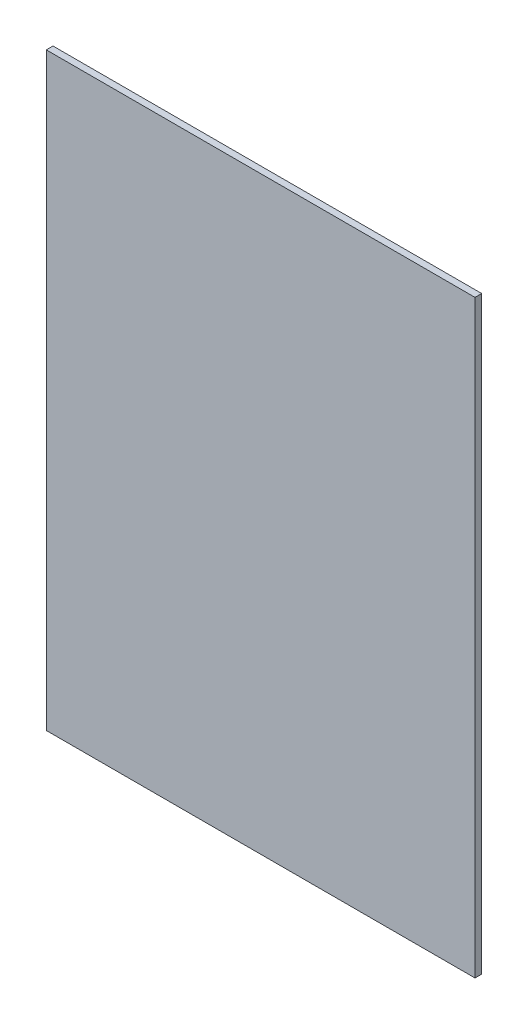
SolidWorks part; units mm, degrees
ref_plane "Front Plane" through (0, 0, 0) normal (0, 0, 1) x (1, 0, 0)
ref_plane "Top Plane" through (0, 0, 0) normal (0, 1, 0) x (1, 0, 0)
ref_plane "Right Plane" through (0, 0, 0) normal (1, 0, 0) x (0, 0, -1)
sketch "Sketch1" plane through (0, 0, 0) normal (0, 0, 1) x (1, 0, 0)
  line L1 (0, 0) -> (203.2, 0)
  line L2 (0, 0) -> (0, 279.4)
  line L3 (0, 279.4) -> (203.2, 279.4)
  line L4 (203.2, 0) -> (203.2, 279.4)
  dimension "D1" = 279.4
  dimension "D2" = 203.2
extrude "Boss-Extrude4" add sketch "Sketch1" along normal blind 3.175 contours L2 L1 L4 L3
sketch "Sketch2" plane through (0, 0, 0) normal (0, 0, -1) x (-1, 0, 0)
  line L1 (-31.3936, 249.2049) -> (-2.1836, 249.2049)
  line L2 (-31.3936, 249.2049) -> (-31.3936, 255.5549)
  line L3 (-31.3936, 255.5549) -> (-2.1836, 255.5549)
  line L4 (-2.1836, 249.2049) -> (-2.1836, 255.5549)
  line L26 (-121.6341, 269.3831) -> (-96.2341, 269.3831)
  line L27 (-121.6341, 269.3831) -> (-121.6341, 275.6569)
  line L28 (-121.6341, 275.6569) -> (-96.2341, 275.6569)
  line L29 (-96.2341, 269.3831) -> (-96.2341, 275.6569)
  line L31 (-95.0721, 245.7573) -> (-84.9121, 245.7573)
  line L32 (-95.0721, 245.7573) -> (-95.0721, 261.7593)
  line L33 (-95.0721, 261.7593) -> (-84.9121, 261.7593)
  line L34 (-84.9121, 245.7573) -> (-84.9121, 261.7593)
  line L35 (-89.1031, 253.8853) -> (-86.1821, 253.8853)
  line L36 (-89.1031, 253.8853) -> (-89.1031, 247.5353)
  line L37 (-89.1031, 247.5353) -> (-86.1821, 247.5353)
  line L38 (-86.1821, 253.8853) -> (-86.1821, 247.5353)
  line L40 (-112.6436, 266.3285) -> (-107.5636, 266.3285)
  line L41 (-112.6436, 266.3285) -> (-112.6436, 234.5785)
  line L42 (-112.6436, 234.5785) -> (-107.5636, 234.5785)
  line L43 (-107.5636, 266.3285) -> (-107.5636, 234.5785)
  line L44 (-138.0871, 270.3021) -> (-161.5231, 278.0823)
  line L45 (-161.5231, 278.0823) -> (-170.4131, 270.4623)
  line L46 (-170.4131, 270.4623) -> (-170.4131, 262.3343)
  line L47 (-170.4131, 262.3343) -> (-166.5711, 262.3343)
  line L48 (-166.5711, 262.3343) -> (-166.5711, 265.9961)
  line L49 (-166.5711, 265.9961) -> (-161.7499, 270.1286)
  line L50 (-161.7499, 270.1286) -> (-140.4879, 263.0702)
  line L51 (-140.4879, 263.0702) -> (-138.0871, 270.3021)
  line L61 (-186.5536, 277.0345) -> (-178.4256, 277.0345)
  line L62 (-186.5536, 277.0345) -> (-186.5536, 246.5545)
  line L63 (-186.5536, 246.5545) -> (-178.4256, 246.5545)
  line L64 (-178.4256, 277.0345) -> (-178.4256, 246.5545)
  line L80 (-49.3409, 261.2356) -> (-49.3409, 277.1106)
  line L81 (-49.3409, 261.2356) -> (-78.5509, 261.2356)
  line L82 (-78.5509, 261.2356) -> (-78.5509, 269.4899)
  line L83 (-78.5509, 269.4899) -> (-56.9609, 269.4899)
  line L84 (-56.9609, 269.4899) -> (-56.9609, 277.1106)
  line L85 (-56.9609, 277.1106) -> (-49.3409, 277.1106)
  line L86 (-54.8019, 269.3636) -> (-51.8809, 269.3636)
  line L87 (-54.8019, 269.3636) -> (-54.8019, 263.0136)
  line L88 (-54.8019, 263.0136) -> (-51.8809, 263.0136)
  line L89 (-51.8809, 269.3636) -> (-51.8809, 263.0136)
  line L91 (-57.5959, 262.7596) -> (-75.3759, 262.7596)
  line L92 (-57.5959, 262.7596) -> (-57.5959, 265.6806)
  line L93 (-57.5959, 265.6806) -> (-75.3759, 265.6806)
  line L94 (-75.3759, 262.7596) -> (-75.3759, 265.6806)
  line L98 (-31.4092, 264.742) -> (-2.1283, 264.742)
  line L99 (-31.4092, 264.742) -> (-31.4092, 271.1591)
  line L100 (-31.4092, 271.1591) -> (-2.1283, 271.1591)
  line L101 (-2.1283, 264.742) -> (-2.1283, 271.1591)
  line L102 (-31.3383, 256.868) -> (-2.1283, 256.868)
  line L103 (-31.3383, 256.868) -> (-31.3383, 263.218)
  line L104 (-31.3383, 263.218) -> (-2.1283, 263.218)
  line L105 (-2.1283, 256.868) -> (-2.1283, 263.218)
  line L106 (-198.4619, 276.9896) -> (-190.3339, 276.9896)
  line L107 (-198.4619, 276.9896) -> (-198.4619, 246.5096)
  line L108 (-198.4619, 246.5096) -> (-190.3339, 246.5096)
  line L109 (-190.3339, 276.9896) -> (-190.3339, 246.5096)
  line L114 (-147.2846, 270.8129) -> (-154.9986, 273.3738)
  line L115 (-154.9986, 273.3738) -> (-155.9189, 270.6016)
  line L116 (-155.9189, 270.6016) -> (-148.2049, 268.0407)
  line L117 (-148.2049, 268.0407) -> (-147.2846, 270.8129)
  line L142 (-137.3707, 254.5027) -> (-160.8068, 262.2829)
  line L143 (-160.8068, 262.2829) -> (-169.6968, 254.6629)
  line L144 (-169.6968, 254.6629) -> (-169.6968, 246.5349)
  line L145 (-169.6968, 246.5349) -> (-165.8547, 246.5349)
  line L146 (-165.8547, 246.5349) -> (-165.8547, 250.1967)
  line L147 (-165.8547, 250.1967) -> (-161.0335, 254.3293)
  line L148 (-161.0335, 254.3293) -> (-139.7715, 247.2708)
  line L149 (-139.7715, 247.2708) -> (-137.3707, 254.5027)
  line L150 (-146.5682, 255.0136) -> (-154.2822, 257.5744)
  line L151 (-154.2822, 257.5744) -> (-155.2025, 254.8022)
  line L152 (-155.2025, 254.8022) -> (-147.4885, 252.2413)
  line L153 (-147.4885, 252.2413) -> (-146.5682, 255.0136)
  line L154 (-38.8678, 248.1401) -> (-38.8678, 264.0151)
  line L155 (-38.8678, 248.1401) -> (-68.0778, 248.1401)
  line L156 (-68.0778, 248.1401) -> (-68.0778, 256.3944)
  line L157 (-68.0778, 256.3944) -> (-46.4878, 256.3944)
  line L158 (-46.4878, 256.3944) -> (-46.4878, 264.0151)
  line L159 (-46.4878, 264.0151) -> (-38.8678, 264.0151)
  line L160 (-44.3288, 256.2681) -> (-41.4078, 256.2681)
  line L161 (-44.3288, 256.2681) -> (-44.3288, 249.9181)
  line L162 (-44.3288, 249.9181) -> (-41.4078, 249.9181)
  line L163 (-41.4078, 256.2681) -> (-41.4078, 249.9181)
  line L164 (-47.1228, 249.6641) -> (-64.9028, 249.6641)
  line L165 (-47.1228, 249.6641) -> (-47.1228, 252.5851)
  line L166 (-47.1228, 252.5851) -> (-64.9028, 252.5851)
  line L167 (-64.9028, 249.6641) -> (-64.9028, 252.5851)
  circle A0 centre (-87.4521, 258.4573) radius 1.3335
  circle A1 centre (-110.1036, 262.5185) radius 1.3335
  circle A2 centre (-110.1036, 238.3885) radius 1.3335
  circle A3 centre (-142.3008, 267.6865) radius 1.143
  circle A7 centre (-53.1509, 273.9356) radius 1.143
  circle A8 centre (-186.6959, 261.7275) radius 0.635
  circle A11 centre (-92.5321, 249.5673) radius 1.3335
  circle A12 centre (-141.5844, 251.8871) radius 1.143
  circle A13 centre (-42.6778, 260.8401) radius 1.143
  dimension "D23" = 2.667
  dimension "D24" = 2.54
  dimension "D26" = 2.667
  dimension "D28" = 3.81
  dimension "D30" = 2.286
  dimension "D31" = 2.286
  dimension "D32" = 2.286
  dimension "D33" = 3.175
  dimension "D34" = 2.921
  dimension "D38" = 3.81
  dimension "D40" = 3.175
  dimension "D41" = 6.35
  dimension "D13" = 8.128
  dimension "D60" = 2.921
  dimension "D62" = 2.286
  dimension "D42" = 31.75
  dimension "D54" = 2.667
  dimension "D55" = 3.302
  dimension "D56" = 12.7
  dimension "D57" = 3.81
  dimension "D58" = 2.54
  dimension "D59" = 2.54
  dimension "D50" = 2.667
  dimension "D7" = 6.35
  dimension "D8" = 6.4171
  dimension "D9" = 29.2809
  dimension "D10" = 25.4
  dimension "D11" = 6.2738
  dimension "D12" = 17.78
  dimension "D14" = 2.921
  dimension "D15" = 2.921
  dimension "D16" = 8.89
  dimension "D17" = 2.921
  dimension "D18" = 1.27
  dimension "D19" = 10.16
  dimension "D20" = 2.921
  dimension "D21" = 1.778
  dimension "D22" = 6.35
  dimension "D25" = 5.08
  dimension "D27" = 2.54
  dimension "D29" = 3.81
  dimension "D37" = 15.748
  dimension "D39" = 7.62
  dimension "D43" = 30.48
  dimension "D44" = 8.128
  dimension "D45" = 8.128
  dimension "D46" = 8.89
  dimension "D49" = 17.78
  dimension "D53" = 6.35
  dimension "D61" = 2.921
